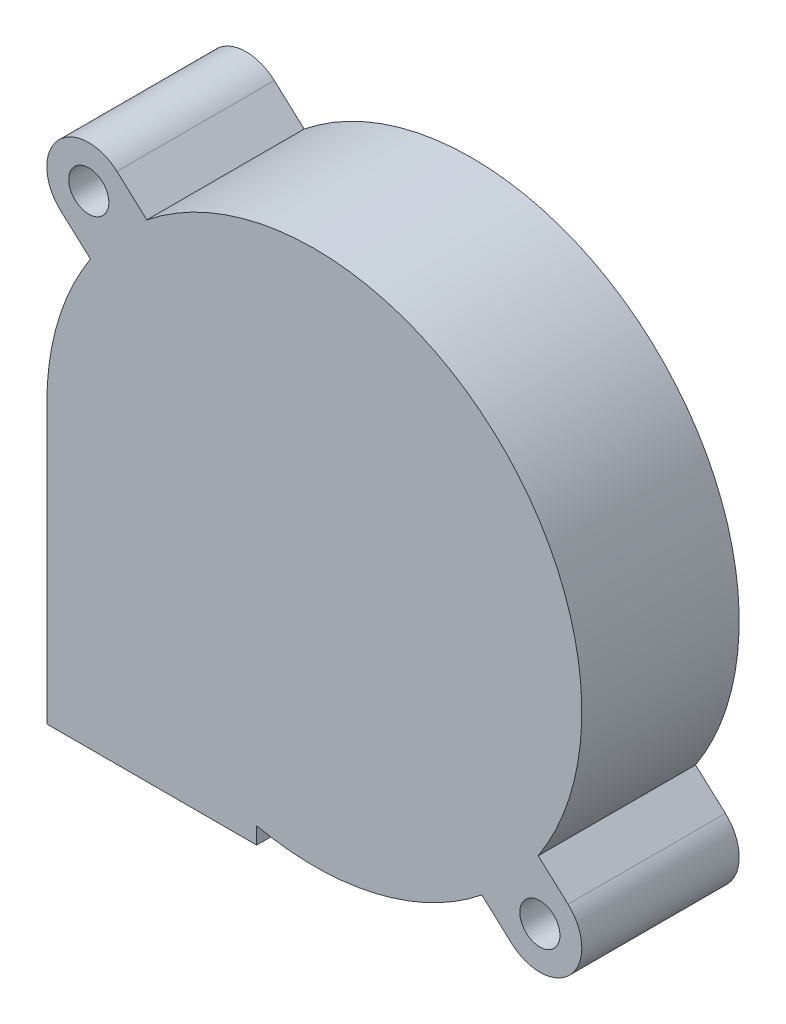
SolidWorks part; units mm, degrees
ref_plane "Спереди" through (0, 0, 0) normal (0, 0, 1) x (1, 0, 0)
ref_plane "Сверху" through (0, 0, 0) normal (0, 1, 0) x (1, 0, 0)
ref_plane "Справа" through (0, 0, 0) normal (1, 0, 0) x (0, 0, -1)
sketch "Эскиз2" plane through (0, 0, 0) normal (0, 0, 1) x (1, 0, 0)
  line L0 (0, 1) -> (40.8676, 1) construction
  line L1 (0, 0) -> (20, 0)
  line L2 (0, 0) -> (0, 26.5)
  line L5 (20, 0) -> (20, 1.6002)
  line L6 (1.3127, 43.0371) -> (44.3127, 4.0371)
  line L7 (6.6873, 48.9629) -> (49.6873, 9.9629)
  line L8 (4, 46) -> (47, 7) construction
  line L9 (25.5, 26.5) -> (51, 26.5) construction
  circle A0 centre (25.5, 26.5) radius 25.5
  circle A1 centre (4, 46) radius 4
  circle A2 centre (47, 7) radius 4
  circle A3 centre (4, 46) radius 1.9128
  circle A4 centre (47, 7) radius 1.9128
  dimension "D1" = 46
  dimension "D2" = 7
  dimension "D5" = 8
  dimension "D3" = 20
  dimension "D4" = 47
  dimension "D6" = 4
extrude "Бобышка-Вытянуть1" add sketch "Эскиз2" along normal blind 15 contours A0 L2 L1 L5 | L6 A0 | A2 A0 L7 A1 L6 | L7 A0 | A1 A0 L7 | A0 A1 | A1 L6 A0 | A1 A0 | A2 L7 A0 | A0 A2 | A2 A0 L6 | A2 A0
